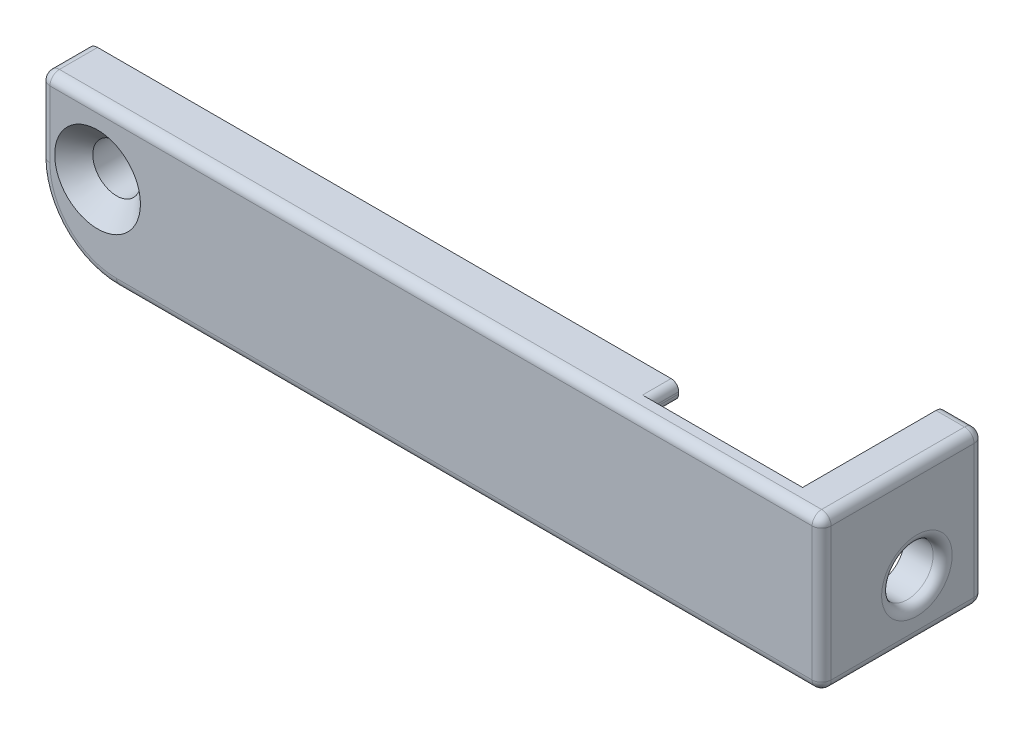
SolidWorks part; units mm, degrees
material "ABS"
ref_plane "前视基准面" through (0, 0, 0) normal (0, 0, 1) x (1, 0, 0)
ref_plane "上视基准面" through (0, 0, 0) normal (0, 1, 0) x (1, 0, 0)
ref_plane "右视基准面" through (0, 0, 0) normal (1, 0, 0) x (0, 0, -1)
sketch "草图1" plane through (0, 0, 0) normal (0, 0, 1) x (1, 0, 0)
  line L1 (19.5, -4) -> (-19.5, -4)
  line L2 (19.5, -4) -> (19.5, 4)
  line L3 (19.5, 4) -> (-19.5, 4)
  line L4 (-19.5, -4) -> (-19.5, 4)
  line L5 (19.5, -4) -> (-19.5, 4) construction
  line L6 (19.5, 4) -> (-19.5, -4) construction
  point P0 (0, 0)
  dimension "D1" = 39
  dimension "D2" = 8
extrude "凸台-拉伸1" add sketch "草图1" along normal blind 1
sketch "草图3" plane through (0, 0, 0) normal (0, 0, -1) x (-1, 0, 0)
  line L0 (19.5, 4) -> (19.5, -4) construction
  line L1 (-19.5, -4) -> (19.5, -4)
  line L2 (-19.5, -4) -> (-19.5, -3.1)
  line L3 (-19.5, -3.1) -> (19.5, -3.1)
  line L4 (19.5, -4) -> (19.5, -3.1)
  dimension "D1" = 0.9
extrude "凸台-拉伸3" add sketch "草图3" along normal blind 1.5
sketch "草图4" plane through (0, 0, 0) normal (0, 0, -1) x (-1, 0, 0)
  line L0 (19.5, 4) -> (19.5, -3.1) construction
  line L1 (-19.5, 4) -> (19.5, 4)
  line L2 (-19.5, 4) -> (-19.5, 3.1)
  line L3 (-19.5, 3.1) -> (19.5, 3.1)
  line L4 (19.5, 4) -> (19.5, 3.1)
  dimension "D1" = 0.9
extrude "凸台-拉伸4" add sketch "草图4" along normal blind 1.5
fillet "圆角1" radius 4 1 edges at (-19.5, -4, -0.25)
sketch "草图5" plane through (19.5, 0, 0) normal (1, 0, 0) x (0, 0, -1)
  line L1 (-1, 4) -> (7.5, 4)
  line L2 (-1, 4) -> (-1, -4)
  line L3 (-1, -4) -> (7.5, -4)
  line L4 (7.5, 4) -> (7.5, -4)
  line L6 (-1, -4) -> (1.5, -4) construction
  dimension "D1" = 8.5
extrude "凸台-拉伸5" add sketch "草图5" along normal blind 2 contours L1 L4 L3 L2
sketch "草图6" plane through (0, 0, -1.5) normal (0, 0, -1) x (-1, 0, 0)
  line L0 (-19.5, 3.1) -> (19.5, 3.1) construction
  line L1 (-19.5, 4) -> (-11.5, 4)
  line L2 (-19.5, 4) -> (-19.5, 3.1)
  line L3 (-19.5, 3.1) -> (-11.5, 3.1)
  line L4 (-11.5, 4) -> (-11.5, 3.1)
  dimension "D1" = 8
extrude "切除-拉伸1" cut sketch "草图6" against normal up to surface (1.5 mm away) up to face at (-7.4282, -0.3432, 0)
fillet "圆角2" radius 0.5 5 edges at (-19.5, 2, 1) (-18.3284, -2.8284, 1) (1, 4, 1) (3, -4, 1) (-19.5, 4, -0.25)
sketch "草图8" plane through (21.5, 0, 0) normal (1, 0, 0) x (0, 0, -1)
  line L0 (-0.5, -4) -> (7.5, -4) construction
  line L1 (-1, 3.5) -> (-1, -3.5) construction
  circle A0 centre (4, -1) radius 1.35
  dimension "D1" = 3
  dimension "D2" = 5
  dimension "D3" = 2.7
extrude "切除-拉伸2" cut sketch "草图8" against normal blind 3
fillet "圆角3" radius 0.5 2 edges at (20.5, 4, -7.5) (20.5, -4, -7.5)
sketch "草图9" plane through (0, 0, 0) normal (0, 0, -1) x (-1, 0, 0)
  line L0 (19.5, 3.1) -> (19.5, 0) construction
  line L1 (19, 4) -> (-11.5, 4) construction
  circle A0 centre (16.5, 0.5) radius 1.1
  dimension "D1" = 3
  dimension "D2" = 3.5
  dimension "D3" = 2.2
extrude "切除-拉伸3" cut sketch "草图9" against normal blind 3
hole_wizard "打孔尺寸(%根据)开槽沉头木螺钉的类型1" positions "3D草图1" profile "草图10" countersink size "M2" standard "GB"
sketch3d "3D草图1"
  line L0 (-16.5, 0.5, 1) -> (-16.5, 0.5, 0) construction
  point P0 (-16.5, 0.5, 1)
sketch "草图10" plane through (-16.5, 0.5, 1) normal (1, 0, 0) x (0, -1, 0)
  line L0 (0, 0) -> (0, 7.6609)
  line L1 (0, 7.6609) -> (1.1, 7)
  line L2 (1.1, 7) -> (1.1, 1.15)
  line L3 (1.1, 1.15) -> (2.25, 0)
  line L5 (2.25, 0) -> (0, 0)
  line L6 (-1.1, 1.15) -> (-2.25, 0) construction
  line L10 (0, 7.6609) -> (-1.1, 7) construction
  line L11 (0, -6.35) -> (0, 107.95) construction
  dimension "孔直径" = 2.2
  dimension "孔深度" = 7
  dimension "近端锥形沉头孔直径" = 4.5
  dimension "近端锥形沉头孔角度" = 90
  dimension "导头角度" = 118
sketch "草图11" plane through (0, 0, -1.5) normal (0, 0, -1) x (-1, 0, 0)
  line L0 (15, 3.1) -> (15, -3.1)
  line L1 (-11.5, 3.1) -> (19.5, 3.1) construction
  line L2 (18.0278, -3.1) -> (-19.5, -3.1) construction
  line L3 (15, -3.1) -> (18.0278, -3.1)
  line L4 (15, 3.1) -> (19.5, 3.1)
  line L5 (19.5, 3.1) -> (19.5, 0)
  arc A0 (18.0278, -3.1) -> (19.5, 0) centre (15.5, 0) ccw construction
  arc A1 (18.0278, -3.1) -> (19.5, 0) centre (15.5, 0) ccw
  circle A2 centre (16.5, 0.5) radius 1.25
  circle A4 centre (16.5, 0.5) radius 1.25 construction
  dimension "D1" = 4.5
extrude "凸台-拉伸6" add sketch "草图11" against normal up to surface (1.5 mm away) up to face at (-15.25, 0.5, 0)
fillet "圆角4" radius 0.5 2 edges at (-15, -3.1, -0.75) (-15, 3.1, -0.75)
fillet "圆角5" radius 0.5 1 edges
fillet "圆角6" radius 0.4 2 edges at (11.5, 4, -0.75) (11.5, 3.1, -0.75)
fillet "圆角7" radius 0.5 9 edges at (21.5, -3.8536, -7.3536) (21.5, -4, -3.25) (21.5, -3.8536, 0.8536) (21.5, 0, 1) (21.5, 3.8536, 0.8536) (21.5, 4, -3.25) (21.5, 3.8536, -7.3536) (21.5, 0, -7.5) (21.5, -1, -5.35)
